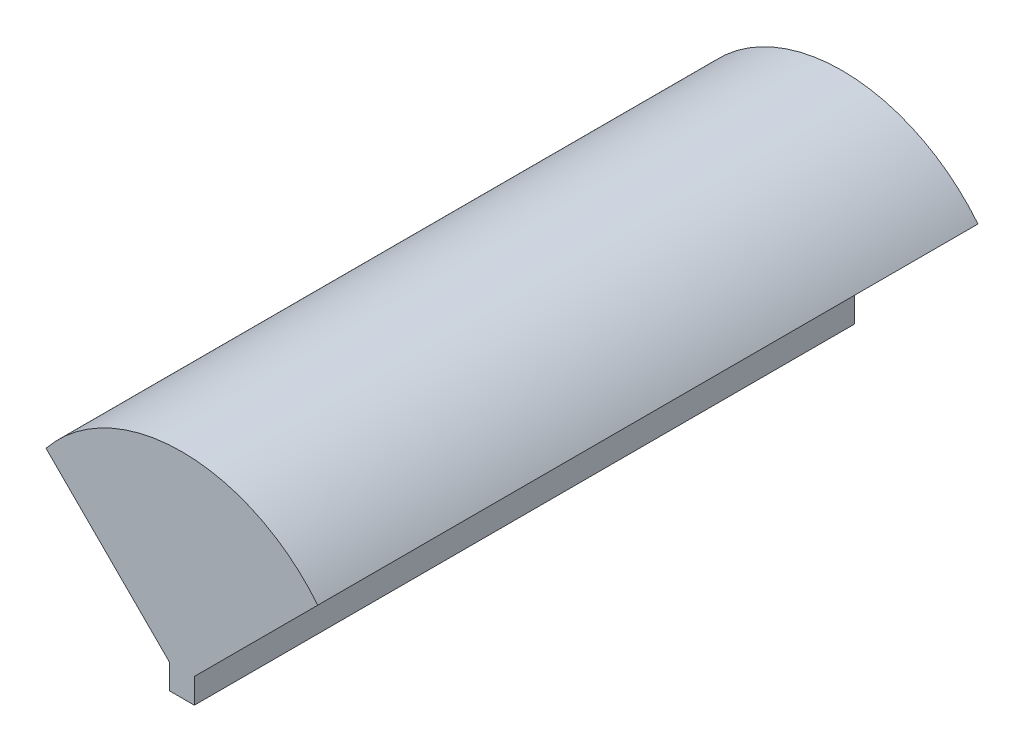
SolidWorks part; units mm, degrees
ref_plane "Front Plane" through (0, 0, 0) normal (0, 0, 1) x (1, 0, 0)
ref_plane "Top Plane" through (0, 0, 0) normal (0, 1, 0) x (1, 0, 0)
ref_plane "Right Plane" through (0, 0, 0) normal (1, 0, 0) x (0, 0, -1)
sketch "Sketch1" plane through (0, 0, 0) normal (0, 0, 1) x (1, 0, 0)
  line L0 (0, 0) -> (0, 2)
  line L1 (0, 0) -> (2, 0)
  line L2 (1, 2.8116) -> (1, -1.1652) construction
  line L3 (2, 0) -> (2, 2)
  line L4 (0, 2) -> (-9.8995, 11.8995)
  line L5 (2, 2) -> (11.8995, 11.8995)
  arc A0 (-9.8995, 11.8995) -> (11.8995, 11.8995) centre (1, 3.1131) cw
  point P7 (1, 0)
  dimension "D5" = 14
  dimension "D1" = 2
  dimension "D2" = 1
  dimension "D3" = 14
  dimension "D4" = 45
extrude "Boss-Extrude1" add sketch "Sketch1" along normal blind 52.96
